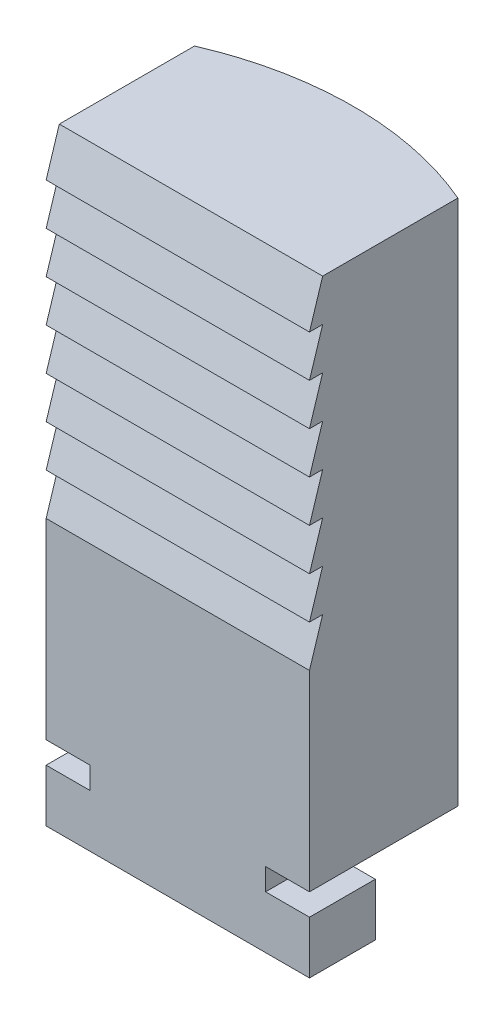
SolidWorks part; units mm, degrees
material "ABS"
ref_plane "Front Plane" through (0, 0, 0) normal (0, 0, 1) x (1, 0, 0)
ref_plane "Top Plane" through (0, 0, 0) normal (0, 1, 0) x (1, 0, 0)
ref_plane "Right Plane" through (0, 0, 0) normal (1, 0, 0) x (0, 0, -1)
sketch "Sketch1" plane through (0, 0, 0) normal (0, 0, 1) x (1, 0, 0)
  line L0 (0, 0) -> (60, 0)
  line L1 (60, 0) -> (60, 12)
  line L2 (60, 12) -> (50, 12)
  line L3 (50, 12) -> (50, 17)
  line L4 (50, 17) -> (60, 17)
  line L5 (60, 17) -> (60, 137)
  line L6 (60, 137) -> (0, 137)
  line L7 (0, 137) -> (0, 17)
  line L8 (0, 17) -> (10, 17)
  line L9 (10, 17) -> (10, 12)
  line L10 (10, 12) -> (0, 12)
  line L11 (0, 12) -> (0, 0)
extrude "Boss-Extrude1" add sketch "Sketch1" along normal blind 40
sketch "Sketch2" plane through (0, 0, 0) normal (1, 0, 0) x (0, 0, -1)
  line L0 (-40, 137) -> (-37, 137)
  line L1 (-40, 137) -> (0, 137) construction
  line L2 (-37, 137) -> (-40, 127.4606)
  line L3 (-40, 17) -> (-40, 137) construction
  line L4 (-40, 127.4606) -> (-37, 127.4606)
  line L5 (-37, 127.4606) -> (-40, 117.9212)
  line L6 (-40, 117.9212) -> (-37, 117.9212)
  line L7 (-37, 117.9212) -> (-40, 108.3818)
  line L8 (-40, 108.3818) -> (-37, 108.3818)
  line L9 (-37, 108.3818) -> (-40, 98.8424)
  line L10 (-40, 98.8424) -> (-37, 98.8424)
  line L11 (-37, 98.8424) -> (-40, 89.303)
  line L12 (-40, 89.303) -> (-37, 89.303)
  line L13 (-37, 89.303) -> (-40, 79.7636)
  line L14 (-40, 79.7636) -> (-37, 79.7636)
  line L15 (-37, 79.7636) -> (-40, 70.2243)
  line L16 (-40, 70.2243) -> (-37, 70.2243)
  line L17 (-37, 70.2243) -> (-40, 60.6849)
  line L18 (-40, 60.6849) -> (-47.7302, 60.6849)
  line L19 (-47.7302, 60.6849) -> (-47.7302, 137)
  line L20 (-47.7302, 137) -> (-40, 137)
extrude "Cut-Extrude1" cut sketch "Sketch2" along normal through all and the other way through all
sketch "Sketch3" plane through (0, 0, 0) normal (0, 0, -1) x (-1, 0, 0)
  line L0 (-60, 0) -> (0, 0)
  line L1 (0, 0) -> (0, 12)
  line L2 (0, 12) -> (-10, 12)
  line L3 (-10, 12) -> (-10, 17)
  line L4 (-10, 17) -> (-50, 17)
  line L5 (-50, 17) -> (-50, 12)
  line L6 (-50, 12) -> (-60, 12)
  line L7 (-60, 12) -> (-60, 0)
extrude "Cut-Extrude2" cut sketch "Sketch3" against normal blind 25
sketch "Sketch4" plane through (0, 137, 0) normal (0, 1, 0) x (1, 0, 0)
  line L0 (60, -37) -> (60, 0) construction
  line L1 (0, -37) -> (0, 0) construction
  line L2 (0, -6.1938) -> (0, 6.0226)
  line L3 (0, 6.0226) -> (60, 6.0226)
  line L4 (60, 6.0226) -> (60, -6.1938)
  arc A0 (60, -6.1938) -> (0, -6.1938) centre (30, -75.7505) ccw
extrude "Cut-Extrude3" cut sketch "Sketch4" against normal through all
